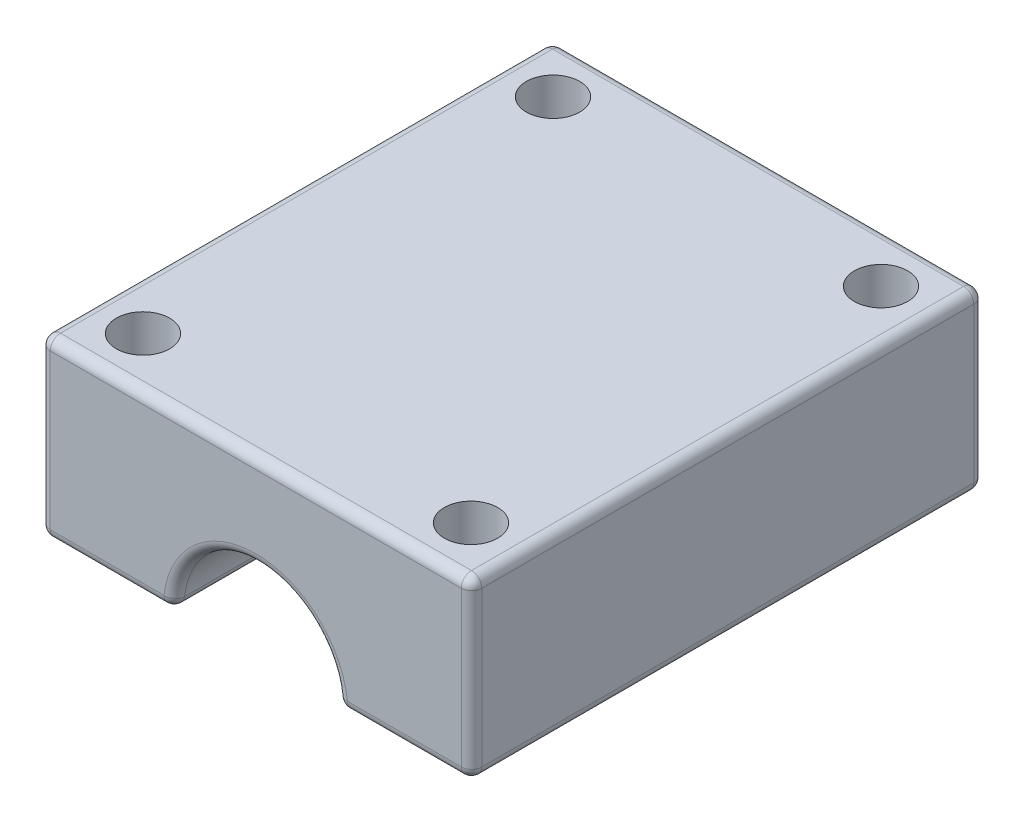
SolidWorks part; units mm, degrees
ref_plane "Front Plane" through (0, 0, 0) normal (0, 0, 1) x (1, 0, 0)
ref_plane "Top Plane" through (0, 0, 0) normal (0, 1, 0) x (1, 0, 0)
ref_plane "Right Plane" through (0, 0, 0) normal (1, 0, 0) x (0, 0, -1)
sketch "Sketch1" plane through (0, 0, 0) normal (0, 1, 0) x (1, 0, 0)
  line L1 (-21.05, -25) -> (21.05, -25)
  line L2 (-21.05, -25) -> (-21.05, 25)
  line L3 (-21.05, 25) -> (21.05, 25)
  line L4 (21.05, -25) -> (21.05, 25)
  line L5 (-21.05, -25) -> (21.05, 25) construction
  line L6 (-21.05, 25) -> (21.05, -25) construction
  point P0 (0, 0)
extrude "Boss-Extrude1" add sketch "Sketch1" along normal blind 17.1
sketch "Sketch2" plane through (0, 17.1, 0) normal (0, 1, 0) x (1, 0, 0)
  circle A0 centre (-16, -20) radius 2.6
extrude "Cut-Extrude1" cut sketch "Sketch2" against normal through all
mirror "Mirror2" about plane through (0, 0, 0) normal (0, 0, 1) of "Cut-Extrude1"
mirror "Mirror3" about plane through (0, 0, 0) normal (1, 0, 0) of "Mirror2", "Cut-Extrude1"
sketch "Sketch3" plane through (0, 0, 25) normal (0, 0, 1) x (1, 0, 0)
  circle A0 centre (0, 0) radius 4.5
extrude "Cut-Extrude2" cut sketch "Sketch3" against normal through all
sketch "Sketch4" plane through (0, 0, 25) normal (0, 0, 1) x (1, 0, 0)
  circle A0 centre (0, 0) radius 8
extrude "Cut-Extrude3" cut sketch "Sketch4" against normal blind 10
fillet "Fillet1" radius 1 24 edges at (-6.25, 0, 15) (6.25, 0, 15) (0, 8, 15) (8, 0, 20) (-8, 0, 20) (21.05, 17.1, 0) (21.05, 0, 0) (-4.5, 0, -5) (4.5, 0, -5) (0, 4.5, 15) (0, 17.1, 25) (21.05, 8.55, 25) (14.525, 0, 25) (0, 8, 25) (-14.525, 0, 25) (-21.05, 17.1, 0) (-21.05, 8.55, 25) (-21.05, 0, 0) (21.05, 8.55, -25) (0, 17.1, -25) (-21.05, 8.55, -25) (-12.775, 0, -25) (0, 4.5, -25) (12.775, 0, -25)
